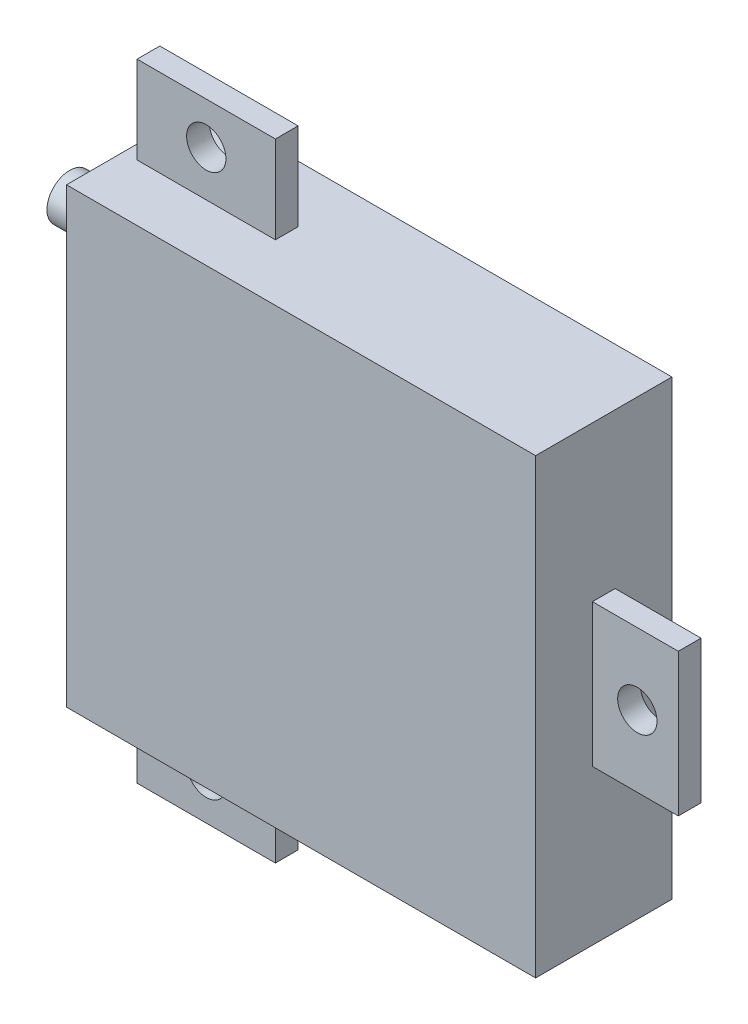
SolidWorks part; units mm, degrees
ref_plane "Front Plane" through (0, 0, 0) normal (0, 0, 1) x (1, 0, 0)
ref_plane "Top Plane" through (0, 0, 0) normal (0, 1, 0) x (1, 0, 0)
ref_plane "Right Plane" through (0, 0, 0) normal (1, 0, 0) x (0, 0, -1)
sketch "Sketch1" plane through (0, 0, 0) normal (0, 0, 1) x (1, 0, 0)
  line L0 (100.1736, 49.3979) -> (132.9142, 49.3979)
  line L1 (132.9142, 49.3979) -> (132.9142, 17.8257)
  line L2 (132.9142, 17.8257) -> (100.1736, 17.8257)
  line L3 (100.1736, 49.3979) -> (100.1736, 17.8257)
extrude "Boss-Extrude1" add sketch "Sketch1" along normal blind 3.9624
sketch "Sketch2" plane through (0, 0, 3.9624) normal (0, 0, 1) x (1, 0, 0)
  line L0 (100.1736, 49.3979) -> (101.1388, 49.3979)
  line L1 (110.7908, 49.3979) -> (132.9142, 49.3979)
  line L2 (132.9142, 49.3979) -> (132.9142, 38.5902)
  line L3 (132.9142, 28.6334) -> (132.9142, 17.8257)
  line L4 (132.9142, 17.8257) -> (110.7908, 17.8257)
  line L5 (101.1388, 17.8257) -> (100.1736, 17.8257)
  line L6 (100.1736, 49.3979) -> (100.1736, 17.8257)
  line L7 (101.1388, 49.3979) -> (101.1388, 55.4939)
  line L8 (110.7908, 49.3979) -> (110.7908, 55.4939)
  line L9 (101.1388, 55.4939) -> (110.7908, 55.4939)
  line L10 (138.9086, 38.5902) -> (138.9086, 28.6334)
  line L11 (132.9142, 28.6334) -> (138.9086, 28.6334)
  line L12 (132.9142, 38.5902) -> (138.9086, 38.5902)
  line L13 (101.1388, 17.8257) -> (101.1388, 11.7297)
  line L14 (110.7908, 17.8257) -> (110.7908, 11.7297)
  line L15 (101.1388, 11.7297) -> (110.7908, 11.7297)
  circle A0 centre (136.051, 33.6118) radius 1.3716
  circle A1 centre (105.9648, 52.5729) radius 1.3716
  circle A2 centre (105.9648, 14.6507) radius 1.3716
extrude "Boss-Extrude2" add sketch "Sketch2" along normal blind 1.5875
sketch "Sketch3" plane through (0, 0, 5.5499) normal (0, 0, 1) x (1, 0, 0)
  line L0 (100.1736, 49.3979) -> (132.9142, 49.3979)
  line L1 (132.9142, 49.3979) -> (132.9142, 17.8257)
  line L2 (132.9142, 17.8257) -> (100.1736, 17.8257)
  line L3 (100.1736, 49.3979) -> (100.1736, 17.8257)
extrude "Boss-Extrude3" add sketch "Sketch3" along normal blind 3.9624
sketch "Sketch4" plane through (100.1736, 0, 0) normal (-1, 0, 0) x (0, 0, 1)
  line L4 (0, 49.3979) -> (0, 17.8257)
  line L5 (0, 17.8257) -> (9.5123, 17.8257)
  line L6 (9.5123, 17.8257) -> (9.5123, 49.3979)
  line L7 (9.5123, 49.3979) -> (0, 49.3979)
  line L8 (0, 49.3979) -> (0, 17.8257) construction
  line L9 (0, 17.8257) -> (9.5123, 17.8257) construction
  line L10 (9.5123, 17.8257) -> (9.5123, 49.3979) construction
  line L11 (9.5123, 49.3979) -> (0, 49.3979) construction
  circle A0 centre (4.5275, 43.8099) radius 1.5875
  point P8 (9.5123, 43.8575)
  dimension "D2" = 5.588
  dimension "D3" = 4.9848
  dimension "D1" = 0
extrude "Boss-Extrude4" add sketch "Sketch4" along normal blind 4.7625
